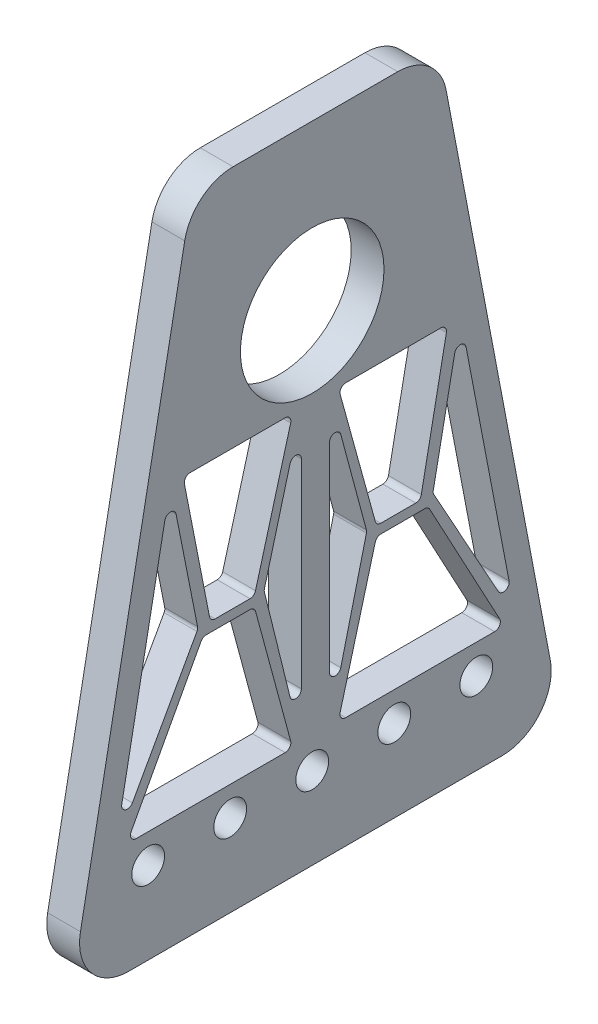
SolidWorks part; units mm, degrees
ref_plane "Front Plane" through (0, 0, 0) normal (0, 0, 1) x (1, 0, 0)
ref_plane "Top Plane" through (0, 0, 0) normal (0, 1, 0) x (1, 0, 0)
ref_plane "Right Plane" through (0, 0, 0) normal (1, 0, 0) x (0, 0, -1)
sketch "Sketch1" plane through (0, 0, 0) normal (1, 0, 0) x (0, 0, -1)
  line L0 (0, 0) -> (76.2, 0)
  line L1 (55, 0) -> (-55, 0) construction
  line L2 (76.2, 0) -> (57.15, 99.7981)
  line L3 (0, 0) -> (19.05, 99.7981)
  line L4 (19.05, 99.7981) -> (57.15, 99.7981)
  circle A0 centre (37.6063, 74.3981) radius 11.1125
  circle A1 centre (37.6063, 12.7) radius 2.54
  circle A2 centre (50.3063, 12.7) radius 2.54
  circle A3 centre (63.0063, 12.7) radius 2.54
  circle A4 centre (24.9063, 12.7) radius 2.54
  circle A5 centre (12.2063, 12.7) radius 2.54
  dimension "D5" = 22.225
  dimension "D7" = 5.08
  dimension "D1" = 101.6
  dimension "D2" = 101.6
  dimension "D3" = 38.1
  dimension "D4" = 76.2
  dimension "D6" = 25.4
  dimension "D8" = 12.7
  dimension "D9" = 3
  dimension "D10" = 3
extrude "Boss-Extrude2" add sketch "Sketch1" along normal blind 5.08
fillet "Fillet1" radius 7.62 4 edges at (2.54, 0, -76.2) (2.54, 0, 0) (2.54, 99.7981, -57.15) (2.54, 99.7981, -19.05)
sketch "Sketch2" plane through (5.08, 0, 0) normal (1, 0, 0) x (0, 0, -1)
  line L0 (38.1, 99.7981) -> (38.1, 0) construction
  line L1 (50.847, 99.7981) -> (25.353, 99.7981) construction
  line L2 (9.2121, 0) -> (66.9879, 0) construction
  line L3 (15.6429, 62.1072) -> (7.0732, 17.4527)
  line L4 (7.0732, 17.4527) -> (19.9165, 40.5707)
  line L5 (19.9165, 40.5707) -> (15.6429, 62.1072)
  line L6 (17.6114, 62.1072) -> (21.8449, 40.5707)
  line L7 (21.8449, 40.5707) -> (28.6475, 40.5707)
  line L8 (28.6475, 40.5707) -> (34.5743, 62.1072)
  line L9 (34.5743, 62.1072) -> (17.6114, 62.1072)
  line L10 (35.9233, 62.1072) -> (30.1471, 40.5707)
  line L11 (30.1471, 40.5707) -> (35.9233, 17.2197)
  line L12 (35.9233, 17.2197) -> (35.9233, 62.1072)
  line L13 (20.6498, 39.1139) -> (28.6547, 39.1139)
  line L14 (28.6547, 39.1139) -> (34.5743, 17.2197)
  line L15 (34.5743, 17.2197) -> (8.8677, 17.2197)
  line L16 (8.8677, 17.2197) -> (20.6498, 39.1139)
  line L17 (46.0529, 40.5707) -> (40.2767, 17.2197)
  line L18 (40.2767, 62.1072) -> (46.0529, 40.5707)
  line L19 (40.2767, 17.2197) -> (40.2767, 62.1072)
  line L20 (41.6257, 17.2197) -> (67.3323, 17.2197)
  line L21 (47.5453, 39.1139) -> (41.6257, 17.2197)
  line L22 (55.5502, 39.1139) -> (47.5453, 39.1139)
  line L23 (67.3323, 17.2197) -> (55.5502, 39.1139)
  line L24 (69.1268, 17.4527) -> (56.2835, 40.5707)
  line L25 (60.5571, 62.1072) -> (69.1268, 17.4527)
  line L26 (56.2835, 40.5707) -> (60.5571, 62.1072)
  line L27 (47.5525, 40.5707) -> (41.6257, 62.1072)
  line L28 (54.3551, 40.5707) -> (47.5525, 40.5707)
  line L29 (58.5886, 62.1072) -> (54.3551, 40.5707)
  line L30 (41.6257, 62.1072) -> (58.5886, 62.1072)
  point P11 (20.6498, 39.1139)
extrude "Cut-Extrude1" cut sketch "Sketch2" against normal through all
fillet "Fillet2" radius 0.889 28 edges at (2.54, 17.4527, -69.1268) (2.54, 40.5707, -56.2835) (2.54, 62.1072, -60.5571) (2.54, 17.2197, -41.6257) (2.54, 40.5707, -47.5525) (2.54, 40.5707, -54.3551) (2.54, 39.1139, -55.5502) (2.54, 62.1072, -58.5886) (2.54, 17.2197, -67.3323) (2.54, 62.1072, -41.6257) (2.54, 39.1139, -47.5453) (2.54, 17.2197, -40.2767) (2.54, 40.5707, -46.0529) (2.54, 62.1072, -40.2767) (2.54, 62.1072, -35.9233) (2.54, 40.5707, -30.1471) (2.54, 17.2197, -35.9233) (2.54, 39.1139, -28.6547) (2.54, 17.2197, -34.5743) (2.54, 17.2197, -8.8677) (2.54, 39.1139, -20.6498) (2.54, 40.5707, -28.6475) (2.54, 40.5707, -21.8449) (2.54, 62.1072, -17.6114) (2.54, 62.1072, -34.5743) (2.54, 17.4527, -7.0732) (2.54, 40.5707, -19.9165) (2.54, 62.1072, -15.6429)
